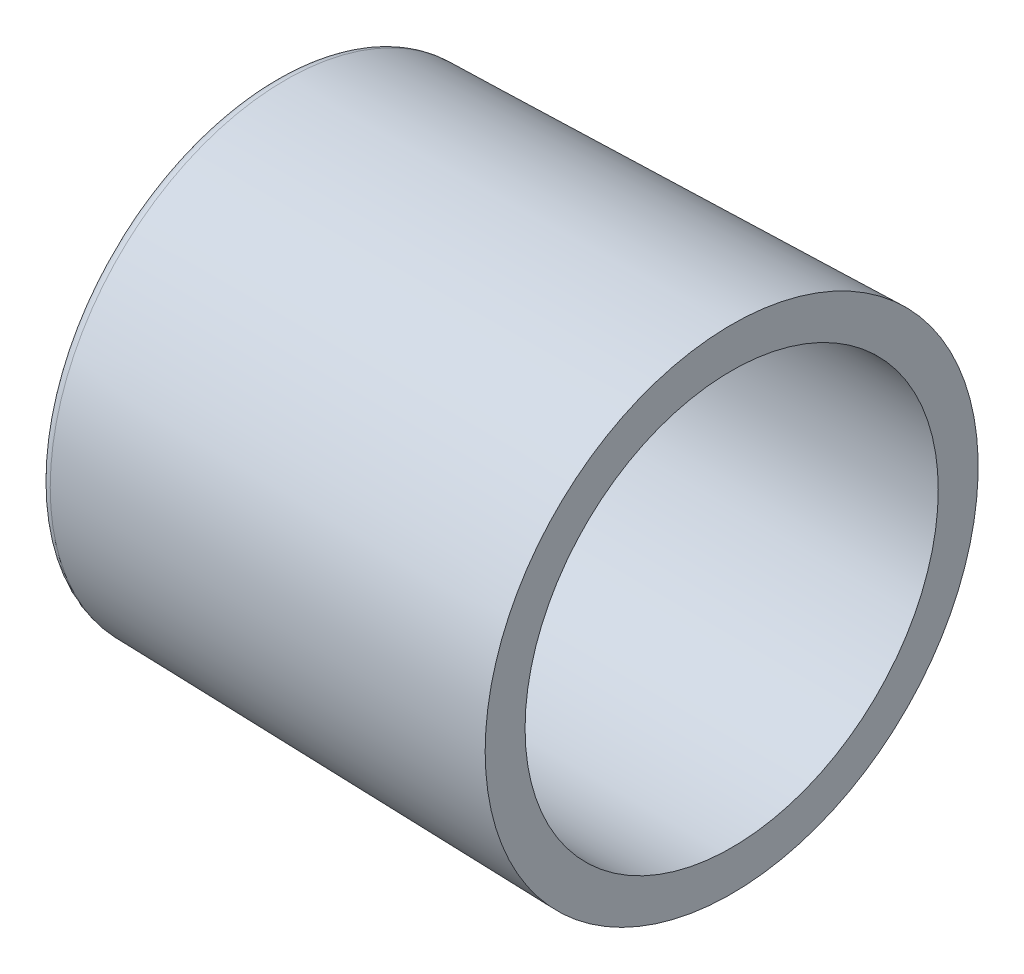
SolidWorks part; units mm, degrees
ref_plane "Front" through (0, 0, 0) normal (0, 0, 1) x (1, 0, 0)
ref_plane "Top" through (0, 0, 0) normal (0, 1, 0) x (1, 0, 0)
ref_plane "Right" through (0, 0, 0) normal (1, 0, 0) x (0, 0, -1)
sketch "Sketch1" plane through (0, 0, 0) normal (0, 0, 1) x (1, 0, 0)
  line L0 (0, 11.185) -> (0, 0) construction
  line L1 (-15.6242, 0) -> (13.4082, 0) construction
  line L2 (6, 11.335) -> (-14.5125, 10.8222)
  line L3 (-15, 10.81) -> (-15, 0) construction
  line L4 (6, 11.335) -> (6, 0) construction
  line L5 (-15, 10.81) -> (6, 10.81) construction
  line L6 (-15, 10.3223) -> (-15, 0) construction
  line L7 (-15, 10.3223) -> (6, 10.3223)
  line L8 (6, 10.3223) -> (6, 11.335)
  line L9 (-14.5125, 10.8222) -> (-15, 10.81) construction
  arc A0 (-14.5125, 10.8222) -> (-15, 10.3223) centre (-14.5, 10.3223) ccw
  dimension "D5" = 0.5
  dimension "D1" = 21
  dimension "D2" = 22.37
  dimension "D3" = 15
  dimension "D4" = 0.525
revolve "Revolve1" add sketch "Sketch1" angle 360 mid plane about L1
ref_plane "Plane1" through (-15, 0, 0) normal (1, 0, 0) x (0, 0, -1)
sketch "Sketch2" plane through (6, 0, 0) normal (1, 0, 0) x (0, 0, -1)
  circle A0 centre (0, 0) radius 9.5
  circle A1 centre (0, 0) radius 10.3223 construction
  circle A2 centre (0, 0) radius 10.3223
  dimension "D1" = 19
extrude "Boss-Extrude1" add sketch "Sketch2" against normal up to surface (111 mm away)
fillet "Fillet1" radius 0.5 1 edges at (-15, 0, -9.5)
sketch "Sketch3" plane through (6, 0, 0) normal (1, 0, 0) x (0, 0, -1)
  circle A0 centre (0, 0) radius 11.335
  circle A1 centre (0, 0) radius 9.5
equation "\"D4@Sketch1\" = \"D1@Sketch1\"/40"
